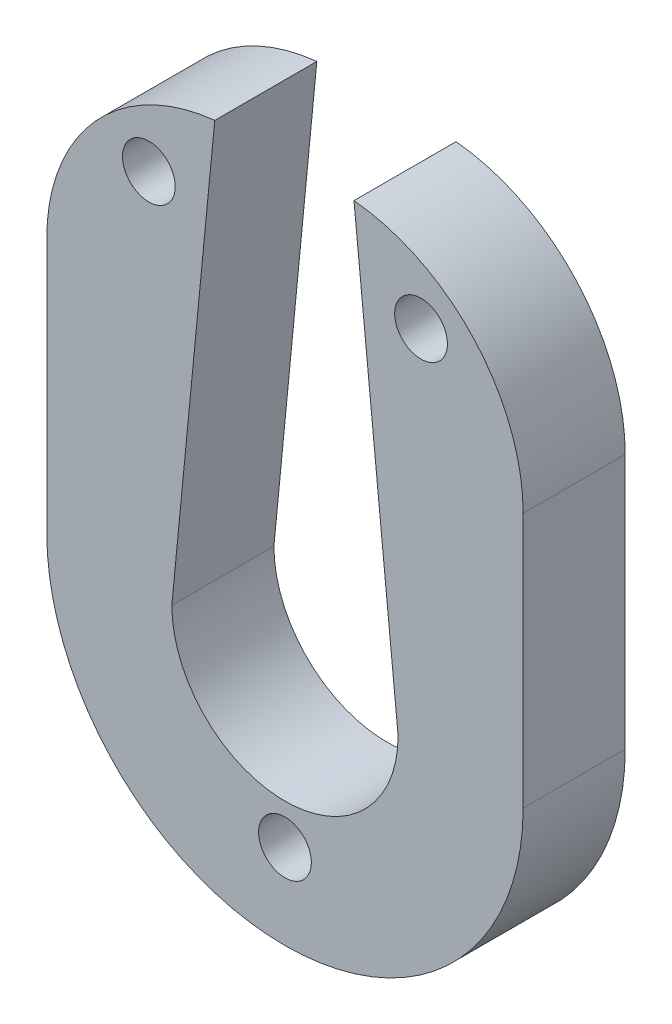
SolidWorks part; units mm, degrees
ref_plane "Płaszczyzna przednia" through (0, 0, 0) normal (0, 0, 1) x (1, 0, 0)
ref_plane "Płaszczyzna górna" through (0, 0, 0) normal (0, 1, 0) x (1, 0, 0)
ref_plane "Płaszczyzna prawa" through (0, 0, 0) normal (1, 0, 0) x (0, 0, -1)
sketch "Szkic1" plane through (0, 0, 0) normal (0, 0, 1) x (1, 0, 0)
  line L6 (-174.1811, 72.9248) -> (-174.1811, 87.9248)
  line L7 (-202.1811, 72.9248) -> (-202.1811, 87.9248)
  line L8 (-191.1811, 98.9248) -> (-185.1811, 98.9248)
  arc A0 (-202.1811, 72.9248) -> (-174.1811, 72.9248) centre (-188.1811, 72.9248) ccw
  arc A1 (-202.1811, 87.9248) -> (-191.1811, 98.9248) centre (-191.1811, 87.9248) cw
  arc A2 (-174.1811, 87.9248) -> (-185.1811, 98.9248) centre (-185.1811, 87.9248) ccw
  dimension "D1" = 28
  dimension "D2" = 26
  dimension "D3" = 11
extrude "Dodanie-wyciągnięcie1" add sketch "Szkic1" against normal blind 6
sketch "Szkic3" plane through (0, 0, 0) normal (0, 0, 1) x (1, 0, 0)
  line L0 (-174.1811, 72.9248) -> (-174.1811, 87.9248) construction
  line L1 (-202.1811, 87.9248) -> (-202.1811, 72.9248) construction
  circle A0 centre (-196.1811, 94.3248) radius 1.55
  circle A1 centre (-180.1811, 94.3248) radius 1.55
  circle A2 centre (-188.1811, 63.9248) radius 1.55
  arc A3 (-184.6207, 102.3297) -> (-191.8207, 102.32) centre (-188.2207, 102.3248) ccw construction
  arc A5 (-202.1811, 72.9248) -> (-174.1811, 72.9248) centre (-188.1811, 72.9248) ccw construction
  dimension "D1" = 0
  dimension "D2" = 6
  dimension "D3" = 6
  dimension "D4" = 8
  dimension "D5" = 3.1
  dimension "D6" = 0
  dimension "D7" = 3.1
  dimension "D8" = 3.1
  dimension "D9" = 9
extrude "Wytnij-wyciągnięcie2" cut sketch "Szkic3" against normal blind 6
sketch "Szkic4" plane through (0, 0, 0) normal (0, 0, 1) x (1, 0, 0)
  circle A0 centre (-188.1811, 72.9248) radius 1.55
  circle A1 centre (-188.1811, 72.9248) radius 4.5 construction
  dimension "D1" = 0
  dimension "D2" = 3.1
extrude "Wytnij-wyciągnięcie3" cut sketch "Szkic4" against normal blind 6
sketch "Szkic6" plane through (0, 0, 0) normal (0, 0, 1) x (1, 0, 0)
  line L0 (-181.5311, 72.9412) -> (-184.4707, 102.3373)
  line L1 (-191.9707, 102.3272) -> (-194.8311, 72.9233)
  line L2 (-191.8207, 102.32) -> (-194.6811, 72.9161)
  line L3 (-181.6811, 72.9336) -> (-184.6207, 102.3297)
  line L4 (-191.8207, 102.32) -> (-194.6811, 72.9161)
  line L5 (-181.6811, 72.9336) -> (-184.6207, 102.3297)
  arc A0 (-184.4707, 102.3373) -> (-191.9707, 102.3272) centre (-188.2207, 102.3248) ccw
  arc A1 (-194.8311, 72.9233) -> (-181.5311, 72.9412) centre (-188.1811, 72.9248) ccw
  arc A2 (-194.6811, 72.9161) -> (-181.6811, 72.9336) centre (-188.1811, 72.9248) ccw
  arc A3 (-184.6207, 102.3297) -> (-191.8207, 102.32) centre (-188.2207, 102.3248) ccw
  arc A4 (-194.6811, 72.9161) -> (-181.6811, 72.9336) centre (-188.1811, 72.9248) ccw
  arc A5 (-184.6207, 102.3297) -> (-191.8207, 102.32) centre (-188.2207, 102.3248) ccw
  dimension "D1" = 0
  dimension "D2" = 0.15
sketch "Szkic7" plane through (0, 0, -6) normal (0, 0, -1) x (-1, 0, 0)
  line L0 (181.5311, 72.9412) -> (184.4707, 102.3373) construction
  line L1 (191.9707, 102.3272) -> (194.8311, 72.9233) construction
  line L2 (181.5311, 72.9412) -> (184.4707, 102.3373)
  line L3 (191.9707, 102.3272) -> (194.8311, 72.9233)
  arc A0 (191.9707, 102.3272) -> (184.4707, 102.3373) centre (188.2207, 102.3248) ccw construction
  arc A1 (181.5311, 72.9412) -> (194.8311, 72.9233) centre (188.1811, 72.9248) ccw construction
  arc A2 (191.9707, 102.3272) -> (184.4707, 102.3373) centre (188.2207, 102.3248) ccw
  arc A3 (181.5311, 72.9412) -> (194.8311, 72.9233) centre (188.1811, 72.9248) ccw
extrude "Wytnij-wyciągnięcie4" cut sketch "Szkic7" against normal blind 6
equation "\"tolerancja_wpusy\"=0.2"
equation "\"dlugosc_wpustu_duzy\"=20"
equation "\"srednica_otworu_M3\"=3.1"
equation "\"szerokosc_nogi_T\"=3.1"
equation "\"dlugosc_T_30\"=11"
equation "\"grubosc_na_nakretke_kwadrat\"=2"
equation "\"szerokosc_na_nakretke_kwadrat\"=5.85"
equation "\"wyokosc_nadstawki_T\"=0.5"
equation "\"dlugosc_T_20_6\"=14"
equation "\"D5@Szkic3\"=\"srednica_otworu_M3\""
equation "\"D7@Szkic3\"=\"srednica_otworu_M3\""
equation "\"D8@Szkic3\"=\"srednica_otworu_M3\""
equation "\"D2@Szkic4\"=\"srednica_otworu_M3\""
